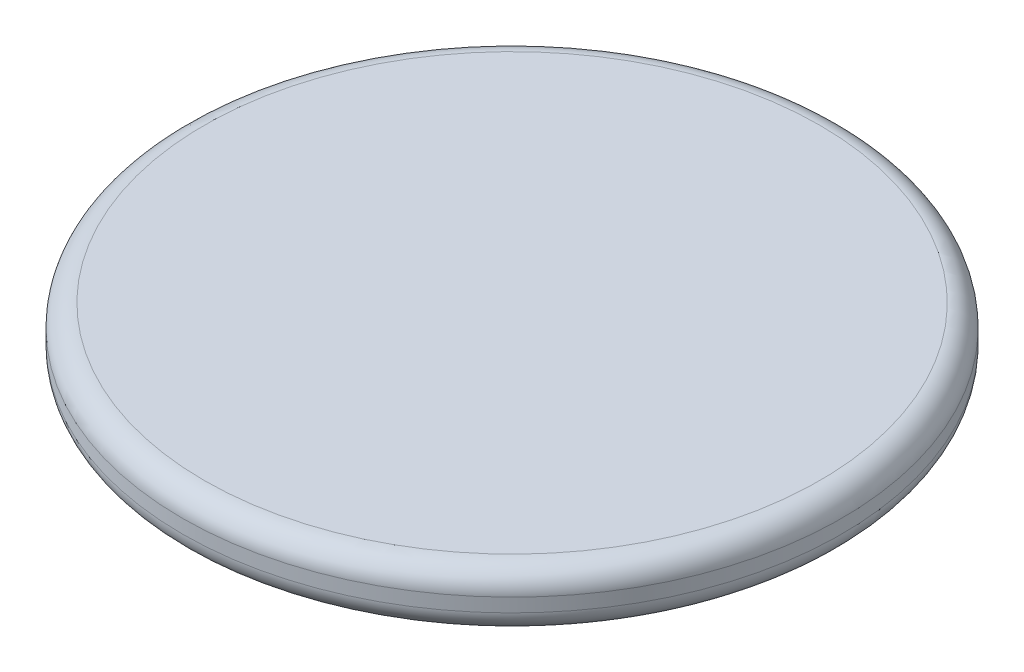
SolidWorks part; units mm, degrees
ref_plane "Front Plane" through (0, 0, 0) normal (0, 0, 1) x (1, 0, 0)
ref_plane "Top Plane" through (0, 0, 0) normal (0, 1, 0) x (1, 0, 0)
ref_plane "Right Plane" through (0, 0, 0) normal (1, 0, 0) x (0, 0, -1)
sketch "Sketch1" plane through (0, 0, 0) normal (0, 1, 0) x (1, 0, 0)
  circle A0 centre (-132.5872, 38.4369) radius 115
extrude "Boss-Extrude4" add sketch "Sketch1" along normal blind 20
sketch "Sketch4" plane through (0, 0, 0) normal (0, -1, 0) x (-1, 0, 0)
  circle A1 centre (131.2639, 37.4444) radius 30
extrude "Boss-Extrude5" add sketch "Sketch4" along normal blind 50
fillet "Fillet1" radius 7.62 2 edges at (-132.5872, 0, 76.5631) (-132.5872, 20, 76.5631)
